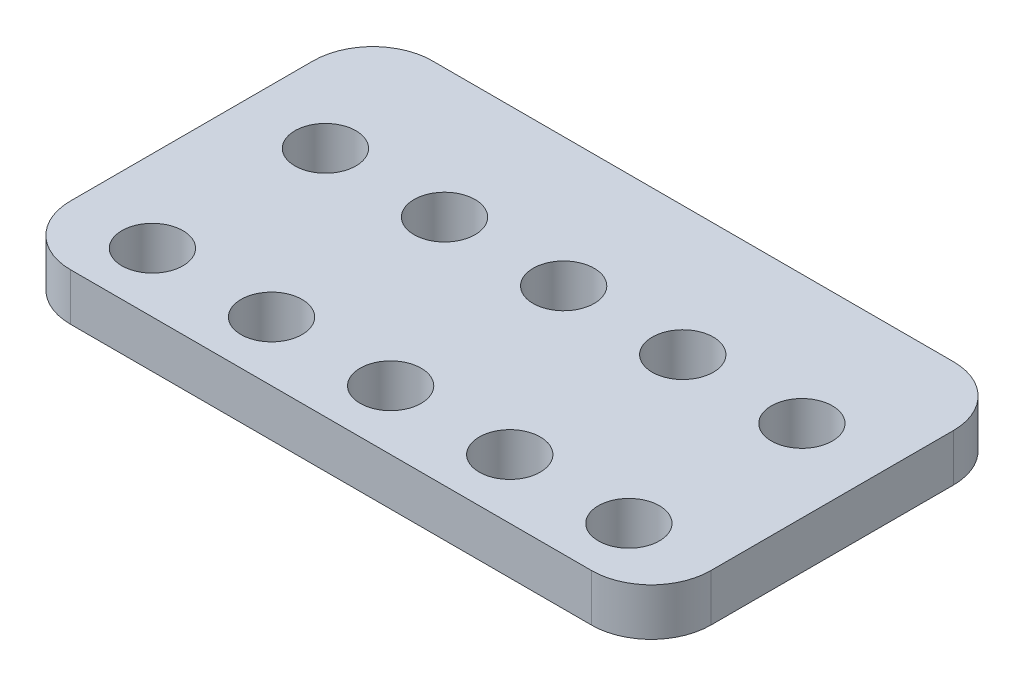
SolidWorks part; units mm, degrees
ref_plane "Front Plane" through (0, 0, 0) normal (0, 0, 1) x (1, 0, 0)
ref_plane "Top Plane" through (0, 0, 0) normal (0, 1, 0) x (1, 0, 0)
ref_plane "Right Plane" through (0, 0, 0) normal (1, 0, 0) x (0, 0, -1)
sketch "Sketch1" plane through (0, 0, 0) normal (0, 1, 0) x (1, 0, 0)
  line L0 (-12.4515, -8.15) -> (49987.5485, -8.15) construction
  line L1 (21.5, -12.15) -> (-21.5, -12.15)
  line L2 (21.5, -12.15) -> (21.5, 12.15)
  line L3 (21.5, 12.15) -> (-21.5, 12.15)
  line L4 (-21.5, -12.15) -> (-21.5, 12.15)
  line L5 (21.5, -12.15) -> (-21.5, 12.15) construction
  line L6 (21.5, 12.15) -> (-21.5, -12.15) construction
  line L7 (-21.5, 3.47) -> (21.5, 3.47) construction
  line L8 (-21.5, 12.15) -> (21.5, 12.15) construction
  line L9 (-21.5, 12.15) -> (-21.5, 14.65) construction
  line L10 (-21.5, 14.65) -> (21.5, 14.65) construction
  line L11 (21.5, 12.15) -> (21.5, 14.65) construction
  line L12 (-16, -8.15) -> (-16, 49991.85) construction
  line L13 (-16, 3.47) -> (-8, 3.47) construction
  circle A0 centre (-16, -8.15) radius 2.05
  circle A1 centre (-8, -8.15) radius 2.05
  circle A2 centre (0, -8.15) radius 2.05
  circle A3 centre (8, -8.15) radius 2.05
  circle A4 centre (16, -8.15) radius 2.05
  circle A5 centre (-16, 3.47) radius 2.05
  circle A6 centre (-8, 3.47) radius 2.05
  circle A7 centre (0, 3.47) radius 2.05
  circle A8 centre (8, 3.47) radius 2.05
  circle A9 centre (16, 3.47) radius 2.05
  point P0 (0, 0)
  dimension "D5" = 4.1
  dimension "D1" = 43
  dimension "D2" = 24.3
  dimension "D3" = 2.5
  dimension "D6" = 5.5
  dimension "D8" = 8
  dimension "D9" = 8.68
  dimension "D11" = 8
  dimension "D4" = 20.3
  dimension "D7" = 5
  dimension "D10" = 5
extrude "Boss-Extrude1" add sketch "Sketch1" along normal blind 3.175
fillet "Fillet1" radius 4 4 edges at (-21.5, 1.5875, -12.15) (21.5, 1.5875, -12.15) (21.5, 1.5875, 12.15) (-21.5, 1.5875, 12.15)
equation "\"h\" = 8 + 12.3 + 4"
equation "\"w\" = 43mm"
equation "\"D1@Sketch1\"=\"w\""
equation "\"D2@Sketch1\"=\"h\""
equation "\"D5@Sketch1\"=4.1mm"
equation "\"thick\"= 3.175"
equation "\"D1@Boss-Extrude1\"=\"thick\""
